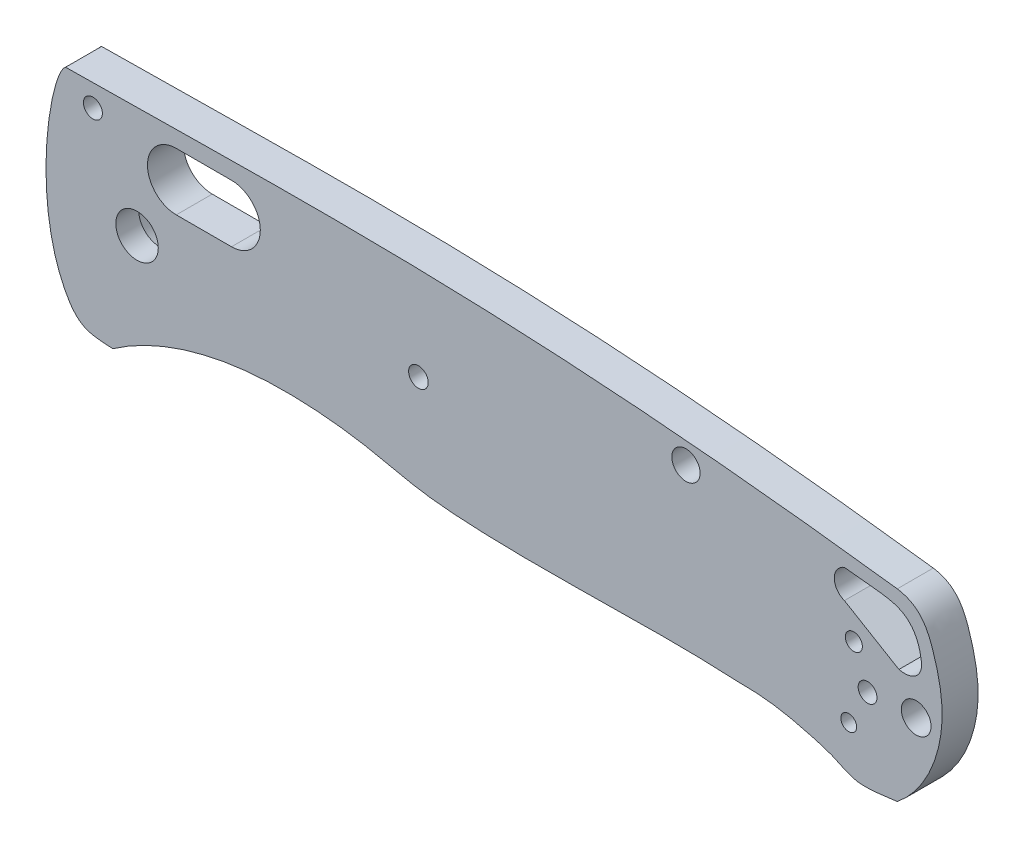
SolidWorks part; units mm, degrees
ref_plane "Front Plane" through (0, 0, 0) normal (0, 0, 1) x (1, 0, 0)
ref_plane "Top Plane" through (0, 0, 0) normal (0, 1, 0) x (1, 0, 0)
ref_plane "Right Plane" through (0, 0, 0) normal (1, 0, 0) x (0, 0, -1)
sketch "Sketch1" plane through (0, 0, 0) normal (0, 0, 1) x (1, 0, 0)
  line L0 (250, 450) -> (1250, 450) construction
  line L1 (28.4032, 61.9785) -> (28.4032, 55.2835) construction
  line L2 (28.4032, 55.2835) -> (34.8377, 55.2835) construction
  line L3 (34.8377, 55.2835) -> (34.8377, 61.9785) construction
  line L4 (34.8377, 61.9785) -> (28.4032, 61.9785) construction
  line L5 (28.4032, 58.631) -> (34.8377, 58.631) construction
  line L6 (28.4032, 61.9836) -> (34.8377, 61.9836)
  line L7 (28.4032, 55.2784) -> (34.8377, 55.2784)
  line L8 (106.213, 55.2835) -> (112.5635, 51.5093)
  arc A0 (28.4032, 61.9836) -> (28.4032, 55.2784) centre (28.4032, 58.631) ccw
  arc A1 (34.8377, 55.2784) -> (34.8377, 61.9836) centre (34.8377, 58.631) ccw
  circle A2 centre (18.6947, 61.202) radius 1.1037
  circle A3 centre (23.8326, 50.8883) radius 2.4738
  circle A4 centre (56.6038, 53.0281) radius 1.1415
  circle A5 centre (87.7623, 59.7233) radius 1.6465
  circle A6 centre (107.31, 51.6867) radius 0.993
  circle A7 centre (108.9115, 47.3786) radius 1.0973
  circle A8 centre (106.7174, 43.2306) radius 0.9197
  circle A9 centre (114.5753, 47.6317) radius 1.733
  arc A10 (106.213, 55.2835) -> (106.213, 58.631) centre (106.8196, 56.9572) cw
  spline S0 degree 3 poles (15.5129, 63.7253) (42.7194, 63.9488) (66.7865, 65.3852) (112.3729, 59.5451) knots 0 0 0 0 1 1 1 1
  spline S1 degree 3 poles (112.3729, 59.5451) (115.0616, 59.1352) (116.7945, 55.3063) (118.4697, 47.2312) (115.6769, 40.7397) (112.3729, 38.0893) knots 0 0 0 0 0.242321 0.484361 1 1 1 1
  spline S2 degree 3 poles (112.3729, 38.0893) (110.8856, 37.8837) (108.6002, 37.6077) (106.511, 38.0288) (105.0819, 38.9171) (100.6213, 40.2121) (97.5826, 40.9475) (93.7284, 40.9051) knots 0 0 0 0 0.125673 0.162909 0.349088 0.435125 1 1 1 1
  spline S3 degree 3 poles (93.7284, 40.9051) (83.4387, 41.479) (70.8371, 40.4501) (56.4192, 41.6045) (50.6714, 43.0935) (43.7188, 43.912) (33.4428, 43.8254) (25.434, 41.165) (21.0117, 38.0893) knots 0 0 0 0 0.42688 0.500374 0.585645 0.66678 0.783695 1 1 1 1
  spline S4 degree 3 poles (21.0117, 38.0893) (19.8106, 38.1503) (17.3676, 38.1379) (11.1539, 47.2772) (13.737, 62.5047) (15.5129, 63.7253) knots 0 0 0 0 0.130513 0.225934 1 1 1 1
  spline S5 degree 3 poles (106.213, 58.631) (109.2087, 58.2258) (113.2404, 58.3696) (114.9824, 55.4242) (115.3359, 52.3125) (114.1377, 51.1763) (112.5635, 51.5093) knots 0 0 0 0 0.426432 0.761667 0.819024 1 1 1 1
  point P26 (31.6205, 58.631)
extrude "Boss-Extrude1" add sketch "Sketch1" along normal blind 4.191
chamfer "Chamfer1" distance 1.524 angle 15 7 edges at (116.3083, 47.6317, 0) (26.3063, 50.8883, 0) (107.6371, 43.2306, 0) (110.0088, 47.3786, 0) (108.3029, 51.6867, 0) (89.4089, 59.7233, 0) (57.7453, 53.0281, 0)
sketch "Sketch2" plane through (0, 0, 0) normal (0, 0, -1) x (-1, 0, 0)
  line L0 (-13.2328, 51.9095) -> (-117.5917, 49.0755) construction
  line L1 (-60.1065, 68.8406) -> (-60.1065, 31.1776) construction
  line L2 (-13.2328, 70.0282) -> (-13.2328, 29.99)
  line L3 (-13.2328, 70.0282) -> (-117.5917, 70.0282)
  line L5 (-13.2328, 29.99) -> (-117.5917, 29.99)
  line L6 (-117.5917, 70.0282) -> (-117.5917, 29.99)
  line L7 (-13.2328, 66.3327) -> (-117.5917, 29.99) construction
  line L8 (-13.2328, 33.6855) -> (-117.5917, 70.0282) construction
  line L9 (-13.2328, 68.8406) -> (-14.5797, 70.0282)
  line L10 (-13.2328, 68.8406) -> (-14.2395, 67.6989)
  line L11 (-14.5797, 70.0282) -> (-15.5864, 68.8865)
  line L12 (-14.2395, 67.6989) -> (-15.5864, 68.8865)
  spline S0 degree 3 poles (-15.5129, 63.7253) (-13.737, 62.5047) (-11.1539, 47.2772) (-17.3676, 38.1379) (-19.8106, 38.1503) (-21.0117, 38.0893) knots 0 0 0 0 0.774066 0.869487 1 1 1 1 construction
  spline S1 degree 3 poles (-112.3729, 38.0893) (-115.6769, 40.7397) (-118.4697, 47.2312) (-116.7945, 55.3063) (-115.0616, 59.1352) (-112.3729, 59.5451) knots 0 0 0 0 0.515639 0.757679 1 1 1 1 construction
  point P8 (-60.1065, 50.0091)
